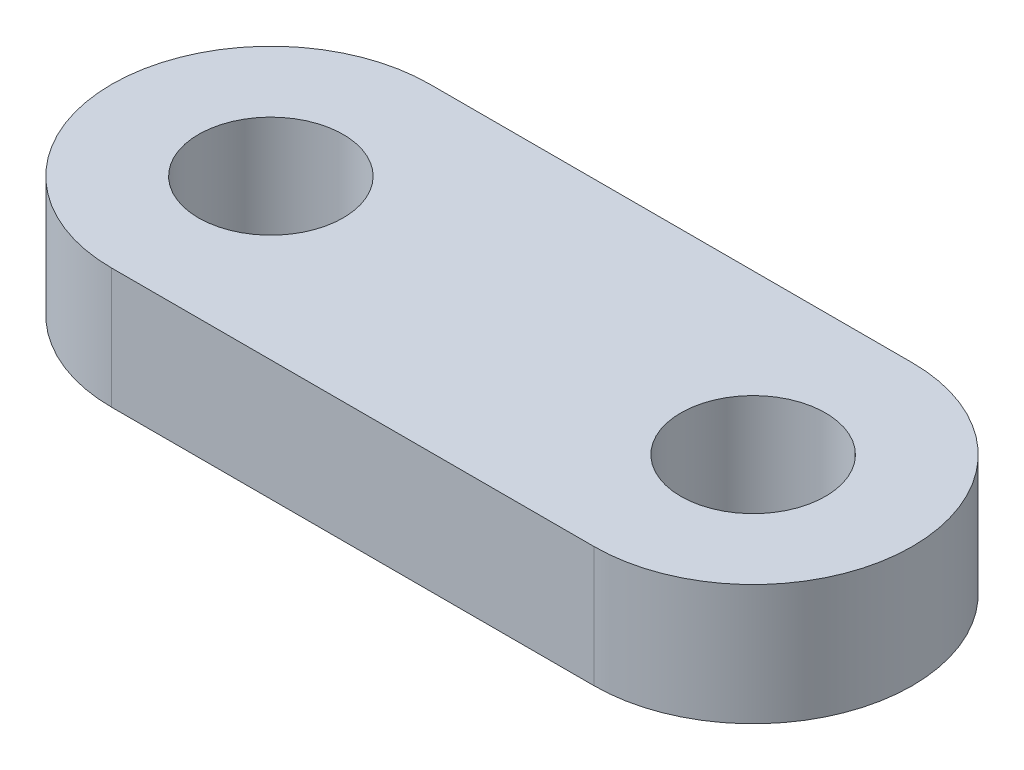
SolidWorks part; units mm, degrees
ref_plane "Front Plane" through (0, 0, 0) normal (0, 0, 1) x (1, 0, 0)
ref_plane "Top Plane" through (0, 0, 0) normal (0, 1, 0) x (1, 0, 0)
ref_plane "Right Plane" through (0, 0, 0) normal (1, 0, 0) x (0, 0, -1)
sketch "Sketch2" plane through (0, 0, 0) normal (0, 1, 0) x (1, 0, 0)
  line L0 (0, 0) -> (50.8, 0)
  line L1 (0, 0) -> (50.8, 0) construction
  line L2 (0, 16.764) -> (50.8, 16.764)
  line L3 (0, -16.764) -> (50.8, -16.764)
  arc A0 (0, 16.764) -> (0, -16.764) centre (0, 0) ccw
  arc A1 (50.8, -16.764) -> (50.8, 16.764) centre (50.8, 0) ccw
  circle A2 centre (0, 0) radius 7.62
  circle A3 centre (50.8, 0) radius 7.62
  point P3 (25.4, 0)
  dimension "D2" = 16.764
  dimension "D1" = 50.8
extrude "Boss-Extrude1" add sketch "Sketch2" along normal blind 12.7
